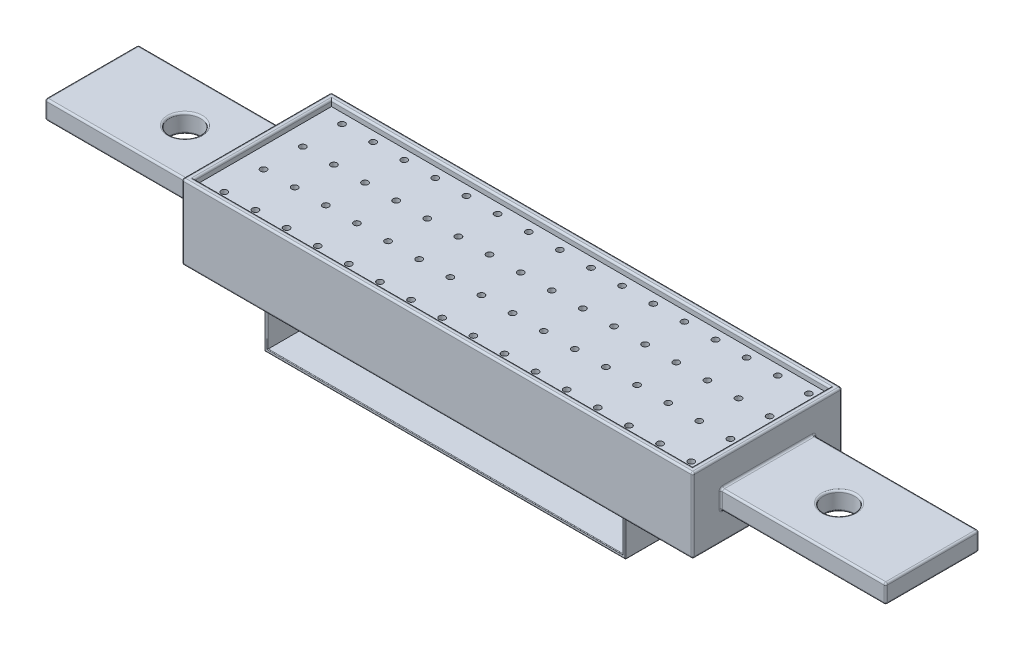
SolidWorks part; units mm, degrees
ref_plane "Front Plane" through (0, 0, 0) normal (0, 0, 1) x (1, 0, 0)
ref_plane "Top Plane" through (0, 0, 0) normal (0, 1, 0) x (1, 0, 0)
ref_plane "Right Plane" through (0, 0, 0) normal (1, 0, 0) x (0, 0, -1)
sketch "Sketch1" plane through (0, 0, 0) normal (0, 1, 0) x (1, 0, 0)
  line L0 (78.2767, 1.5106) -> (73.2767, 1.5106) construction
  line L1 (0, 0) -> (80, 0)
  line L2 (0, 0) -> (0, 22)
  line L3 (0, 22) -> (80, 22)
  line L4 (80, 0) -> (80, 22)
  circle A0 centre (78.2767, 1.5106) radius 0.5
  circle A1 centre (73.2767, 1.5106) radius 0.5
  circle A2 centre (68.2767, 1.5106) radius 0.5
  circle A3 centre (63.2767, 1.5106) radius 0.5
  circle A4 centre (58.2767, 1.5106) radius 0.5
  circle A5 centre (53.2767, 1.5106) radius 0.5
  circle A6 centre (48.2767, 1.5106) radius 0.5
  circle A7 centre (43.2767, 1.5106) radius 0.5
  circle A8 centre (38.2767, 1.5106) radius 0.5
  circle A9 centre (33.2767, 1.5106) radius 0.5
  circle A10 centre (28.2767, 1.5106) radius 0.5
  circle A11 centre (23.2767, 1.5106) radius 0.5
  circle A12 centre (18.2767, 1.5106) radius 0.5
  circle A13 centre (13.2767, 1.5106) radius 0.5
  circle A14 centre (8.2767, 1.5106) radius 0.5
  circle A15 centre (3.2767, 1.5106) radius 0.5
  circle A16 centre (73.2767, 7.8106) radius 0.5
  circle A17 centre (68.2767, 7.8106) radius 0.5
  circle A18 centre (63.2767, 7.8106) radius 0.5
  circle A19 centre (58.2767, 7.8106) radius 0.5
  circle A20 centre (53.2767, 7.8106) radius 0.5
  circle A21 centre (48.2767, 7.8106) radius 0.5
  circle A22 centre (43.2767, 7.8106) radius 0.5
  circle A23 centre (38.2767, 7.8106) radius 0.5
  circle A24 centre (33.2767, 7.8106) radius 0.5
  circle A25 centre (28.2767, 7.8106) radius 0.5
  circle A26 centre (23.2767, 7.8106) radius 0.5
  circle A27 centre (18.2767, 7.8106) radius 0.5
  circle A28 centre (13.2767, 7.8106) radius 0.5
  circle A29 centre (8.2767, 7.8106) radius 0.5
  circle A30 centre (3.2767, 7.8106) radius 0.5
  circle A31 centre (73.2767, 14.1106) radius 0.5
  circle A32 centre (68.2767, 14.1106) radius 0.5
  circle A33 centre (63.2767, 14.1106) radius 0.5
  circle A34 centre (58.2767, 14.1106) radius 0.5
  circle A35 centre (53.2767, 14.1106) radius 0.5
  circle A36 centre (48.2767, 14.1106) radius 0.5
  circle A37 centre (43.2767, 14.1106) radius 0.5
  circle A38 centre (38.2767, 14.1106) radius 0.5
  circle A39 centre (33.2767, 14.1106) radius 0.5
  circle A40 centre (28.2767, 14.1106) radius 0.5
  circle A41 centre (23.2767, 14.1106) radius 0.5
  circle A42 centre (18.2767, 14.1106) radius 0.5
  circle A43 centre (13.2767, 14.1106) radius 0.5
  circle A44 centre (8.2767, 14.1106) radius 0.5
  circle A45 centre (3.2767, 14.1106) radius 0.5
  circle A46 centre (73.2767, 20.4106) radius 0.5
  circle A47 centre (68.2767, 20.4106) radius 0.5
  circle A48 centre (63.2767, 20.4106) radius 0.5
  circle A49 centre (58.2767, 20.4106) radius 0.5
  circle A50 centre (53.2767, 20.4106) radius 0.5
  circle A51 centre (48.2767, 20.4106) radius 0.5
  circle A52 centre (43.2767, 20.4106) radius 0.5
  circle A53 centre (38.2767, 20.4106) radius 0.5
  circle A54 centre (33.2767, 20.4106) radius 0.5
  circle A55 centre (28.2767, 20.4106) radius 0.5
  circle A56 centre (23.2767, 20.4106) radius 0.5
  circle A57 centre (18.2767, 20.4106) radius 0.5
  circle A58 centre (13.2767, 20.4106) radius 0.5
  circle A59 centre (8.2767, 20.4106) radius 0.5
  circle A60 centre (3.2767, 20.4106) radius 0.5
  circle A61 centre (78.2767, 7.8106) radius 0.5
  circle A62 centre (78.2767, 14.1106) radius 0.5
  circle A63 centre (78.2767, 20.4106) radius 0.5
  dimension "D3" = 16
  dimension "D1" = 80
  dimension "D2" = 22
  dimension "D4" = 4
extrude "Boss-Extrude1" add sketch "Sketch1" along normal blind 10
ref_plane "Plane1" through (0, 0, -11) normal (0, 0, 1) x (1, 0, 0)
sketch "Sketch3" plane through (0, 0, -11) normal (0, 0, 1) x (1, 0, 0)
  line L0 (39.9624, 10.6892) -> (39.9624, -0.4686) construction
  point P3 (39.9624, 10.6892)
  point P4 (39.9624, -0.4686)
sketch "Sketch6" plane through (0, 0, 0) normal (0, 1, 0) x (1, 0, 0)
  line L1 (80, 0) -> (0, 0)
  line L2 (80, 0) -> (80, 22)
  line L3 (80, 22) -> (0, 22)
  line L4 (0, 0) -> (0, 22)
  line L5 (80.9624, 23) -> (-1.0376, 23)
  line L6 (80.9624, 23) -> (80.9624, -1)
  line L7 (80.9624, -1) -> (-1.0376, -1)
  line L8 (-1.0376, 23) -> (-1.0376, -1)
  line L9 (80.9624, 23) -> (-1.0376, -1) construction
  line L10 (80.9624, -1) -> (-1.0376, 23) construction
  point P6 (39.9624, 11)
  dimension "D1" = 82
  dimension "D2" = 24
extrude "Boss-Extrude2" add sketch "Sketch6" along normal blind 11 and the other way blind 1
sketch "Sketch7" plane through (-1.0376, 0, 0) normal (-1, 0, 0) x (0, 0, 1)
  line L0 (-11, 10.6892) -> (-11, -0.4686) construction
  line L1 (-18.5, 6.6103) -> (-3.5, 6.6103)
  line L2 (-18.5, 6.6103) -> (-18.5, 3.6103)
  line L3 (-18.5, 3.6103) -> (-3.5, 3.6103)
  line L4 (-3.5, 6.6103) -> (-3.5, 3.6103)
  line L5 (-18.5, 6.6103) -> (-3.5, 3.6103) construction
  line L6 (-18.5, 3.6103) -> (-3.5, 6.6103) construction
  point P0 (-11, 5.1103)
  dimension "D1" = 3
  dimension "D2" = 15
extrude "Boss-Extrude3" add sketch "Sketch7" along normal blind 26.5
ref_plane "Plane2" through (40, 0, 0) normal (1, 0, 0) x (0, 0, -1)
mirror "Mirror2" about plane through (40, 0, 0) normal (1, 0, 0) of "Boss-Extrude2", "Boss-Extrude3"
sketch "Sketch8" plane through (0, 6.6103, 0) normal (0, 1, 0) x (1, 0, 0)
  circle A0 centre (-12.5376, 11) radius 2.5
  dimension "D1" = 5
extrude "Cut-Extrude1" cut sketch "Sketch8" against normal through all
mirror "Mirror3" about plane through (40, 0, 0) normal (1, 0, 0) of "Cut-Extrude1"
fillet "Fillet1" radius 0.3 48 edges at (-1.0376, 5.1103, -3.5) (-14.2876, 6.6103, -3.5) (-1.0376, 6.6103, -11) (-14.2876, 6.6103, -18.5) (-1.0376, 5.1103, -18.5) (-14.2876, 3.6103, -18.5) (-14.2876, 3.6103, -3.5) (-1.0376, 3.6103, -11) (-27.5376, 3.6103, -11) (-27.5376, 5.1103, -18.5) (-27.5376, 6.6103, -11) (-27.5376, 5.1103, -3.5) (-1.0376, 5, -23) (-1.0376, 5, 1) (40, -1, 0) (0, -1, -11) (40, -1, -22) (80, -1, -11) (40, -1, -23) (-1.0376, -1, -11) (40, -1, 1) (40, 11, -22) (0, 11, -11) (40, 11, 0) (80, 11, -11) (40, 11, 1) (-1.0376, 11, -11) (40, 11, -23) (81.0376, 11, -11) (81.0376, -1, -11) (81.0376, 5, -23) (81.0376, 5, 1) (81.0376, 5.1103, -3.5) (94.2876, 3.6103, -3.5) (81.0376, 3.6103, -11) (92.5376, 3.6103, -13.5) (94.2876, 3.6103, -18.5) (81.0376, 5.1103, -18.5) (94.2876, 6.6103, -18.5) (94.2876, 6.6103, -3.5) (81.0376, 6.6103, -11) (92.5376, 6.6103, -8.5) (107.5376, 6.6103, -11) (107.5376, 5.1103, -18.5) (107.5376, 3.6103, -11) (107.5376, 5.1103, -3.5) (-12.5376, 3.6103, -8.5) (-12.5376, 6.6103, -8.5)
ref_plane "Plane3" through (0, -1, 0) normal (0, 1, 0) x (1, 0, 0)
sketch "Sketch10" plane through (0, -1, 0) normal (0, 1, 0) x (1, 0, 0)
  line L3 (68.6428, 21.6157) -> (10.6428, 21.6157)
  line L4 (68.6428, 21.6157) -> (68.6428, 0.6157)
  line L5 (68.6428, 0.6157) -> (10.6428, 0.6157)
  line L6 (10.6428, 21.6157) -> (10.6428, 0.6157)
  line L7 (68.6428, 21.6157) -> (39.9624, 11) construction
  line L8 (68.6428, 0.6157) -> (10.6428, 21.6157) construction
  point P7 (39.9624, 11)
  dimension "D1" = 21
  dimension "D2" = 58
extrude "Boss-Extrude4" add sketch "Sketch10" against normal blind 7
shell "Shell1" thickness 0.5
fillet "Fillet2" radius 0.1 12 edges at (39.6428, -8, -21.6157) (10.6428, -4.5, -21.6157) (10.6428, -8, -11.1157) (68.6428, -8, -11.1157) (68.6428, -4.5, -21.6157) (68.6428, -4.5, -0.6157) (68.1428, -4.5, -0.6157) (39.6428, -1.5, -0.6157) (39.6428, -7.5, -0.6157) (11.1428, -4.5, -0.6157) (10.6428, -4.5, -0.6157) (39.6428, -8, -0.6157)
